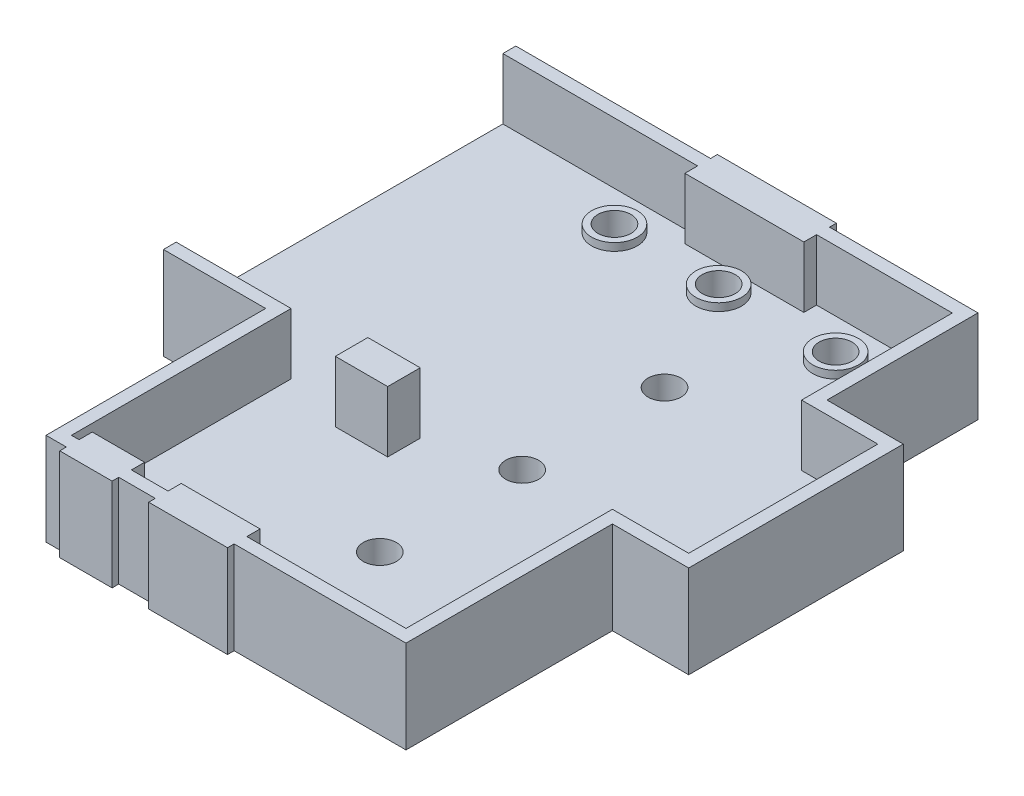
SolidWorks part; units mm, degrees
ref_plane "Спереди" through (0, 0, 0) normal (0, 0, 1) x (1, 0, 0)
ref_plane "Сверху" through (0, 0, 0) normal (0, 1, 0) x (1, 0, 0)
ref_plane "Справа" through (0, 0, 0) normal (1, 0, 0) x (0, 0, -1)
sketch "Эскиз2" plane through (0, 0, 0) normal (0, 1, 0) x (1, 0, 0)
  line L0 (0, 0) -> (-14310, 0) construction
  line L1 (0, 0) -> (0, -10805) construction
  line L2 (0, -3035) -> (-14310, -3035) construction
  line L3 (0, -6485) -> (-14310, -6485) construction
  line L4 (-1500, 0) -> (-1500, -10805) construction
  line L5 (-14310, 0) -> (-14310, -10805) construction
  line L6 (0, -10805) -> (-14310, -10805) construction
  dimension "D1" = 1500
  dimension "D2" = 12810
  dimension "D3" = 3035
  dimension "D4" = 3450
  dimension "D5" = 4320
sketch "Эскиз1" plane through (0, 0, 0) normal (0, 1, 0) x (1, 0, 0)
  line L0 (0, 0) -> (-14310, 0) construction
  line L1 (-1500, 0) -> (-1500, -10805) construction
  line L2 (0, -3035) -> (-14310, -3035) construction
  line L3 (0, 0) -> (0, -10805) construction
  line L4 (0, -6485) -> (-14310, -6485) construction
  line L5 (0, -10805) -> (-14310, -10805) construction
  line L6 (-8010, -6716.1927) -> (-8010, -6425)
  line L7 (-10270, 255) -> (-6440, 255)
  line L8 (-6440, 255) -> (-6440, 390)
  line L9 (-6440, 390) -> (-4100, 390)
  line L10 (-4100, 390) -> (-4100, 255)
  line L11 (-4100, 255) -> (-1180, 255)
  line L12 (-1180, 255) -> (-1180, -2715)
  line L13 (-1180, -2715) -> (320, -2715)
  line L14 (320, -2715) -> (320, -6935)
  line L15 (320, -6935) -> (-1180, -6935)
  line L16 (-1180, -6935) -> (-1180, -10995)
  line L17 (-10270, 255) -> (-10270, 0)
  line L18 (-10270, -6675) -> (-8260, -6675)
  line L19 (-8260, -6675) -> (-8260, -10995)
  line L20 (-1180, -10995) -> (-4560, -10995)
  line L21 (-4560, -10995) -> (-4560, -11125)
  line L22 (-4560, -11125) -> (-6110, -11125)
  line L23 (-6110, -11125) -> (-6110, -10995)
  line L24 (-6110, -10995) -> (-6830, -10995)
  line L25 (-6830, -10995) -> (-6830, -11125)
  line L26 (-6830, -11125) -> (-7860, -11125)
  line L27 (-7860, -11125) -> (-7860, -10995)
  line L28 (-7860, -10995) -> (-8260, -10995)
  line L29 (-10270, 0) -> (-6440, 0)
  line L30 (-1430, 0) -> (-1430, -2965)
  line L31 (-1430, -2965) -> (70, -2965)
  line L32 (70, -2965) -> (70, -6685)
  line L33 (70, -6685) -> (-1430, -6685)
  line L34 (-7860, -10745) -> (-8010, -10745)
  line L35 (-1430, -10745) -> (-4560, -10745)
  line L36 (-8010, -10745) -> (-8010, -6716.1927)
  line L37 (-10270, -6425) -> (-10270, -6675)
  line L38 (-6440, -250) -> (-6440, 0)
  line L39 (-8010, -6425) -> (-10270, -6425)
  line L40 (-6440, -250) -> (-4100, -250)
  line L41 (-7860, -10485) -> (-7860, -10745)
  line L42 (-6760, -6805) -> (-5730, -6805)
  line L43 (-6760, -6805) -> (-6760, -6165)
  line L44 (-6760, -6165) -> (-5730, -6165)
  line L45 (-5730, -6805) -> (-5730, -6165)
  line L46 (-1430, -6685) -> (-1430, -10745)
  line L47 (-4100, 0) -> (-4100, -250)
  line L48 (-4100, 0) -> (-1430, 0)
  line L49 (-6830, -10485) -> (-7860, -10485)
  line L50 (-6830, -10485) -> (-6830, -10745)
  line L51 (-6110, -10745) -> (-6830, -10745)
  line L52 (-6110, -10485) -> (-6110, -10745)
  line L53 (-4560, -10485) -> (-6110, -10485)
  line L54 (-4560, -10485) -> (-4560, -10745)
  dimension "D4" = 255
  dimension "D5" = 2600
  dimension "D6" = 320
  dimension "D7" = 135
  dimension "D8" = 135
  dimension "D9" = 250
  dimension "D10" = 320
  dimension "D11" = 250
  dimension "D12" = 320
  dimension "D13" = 250
  dimension "D14" = 450
  dimension "D15" = 2340
  dimension "D16" = 3830
  dimension "D17" = 250
  dimension "D18" = 250
  dimension "D19" = 130
  dimension "D20" = 130
  dimension "D21" = 1550
  dimension "D22" = 720
  dimension "D23" = 1030
  dimension "D24" = 400
  dimension "D25" = 320
  dimension "D26" = 190
  dimension "D27" = 640
  dimension "D28" = 250
  dimension "D29" = 250
  dimension "D30" = 1030
  dimension "D31" = 60
  dimension "D32" = 250
  dimension "D33" = 3380
  dimension "D34" = 320
  dimension "D35" = 320
  dimension "D36" = 1250
  dimension "D37" = 640
  dimension "D38" = 640
  dimension "D39" = 250
  dimension "D40" = 250
extrude "Бобышка-Вытянуть1" add sketch "Эскиз1" along normal blind 1820
sketch "Эскиз3" plane through (0, 0, 0) normal (0, 1, 0) x (1, 0, 0)
  line L0 (-10270, -6675) -> (-10270, 255)
  line L1 (-10270, 255) -> (-1180, 255)
  line L2 (-1180, 255) -> (-1180, -2715)
  line L3 (-1180, -2715) -> (320, -2715)
  line L4 (320, -2715) -> (320, -6935)
  line L5 (320, -6935) -> (-1180, -6935)
  line L6 (-1180, -6935) -> (-1180, -10995)
  line L7 (-1180, -10995) -> (-8260, -10995)
  line L8 (-8260, -10995) -> (-8260, -6675)
  line L9 (-8260, -6675) -> (-10270, -6675)
  line L10 (-10270, -6675) -> (-9970.5373, -6682.7722)
extrude "Бобышка-Вытянуть2" add sketch "Эскиз3" along normal blind 620 contours L9 L8 L7 L6 L5 L4 L3 L2 L1 L0
sketch "Эскиз5" plane through (0, 0, 0) normal (0, -1, 0) x (1, 0, 0)
  line L0 (-1500, 0) -> (-1500, 10805) construction
  line L1 (0, 0) -> (-14310, 0) construction
  circle A0 centre (-2970, 755) radius 450
  circle A1 centre (-5270, 755) radius 450
  circle A2 centre (-7320, 755) radius 450
  dimension "D3" = 900
  dimension "D4" = 900
  dimension "D5" = 900
  dimension "D6" = 1470
  dimension "D7" = 755
  dimension "D8" = 755
  dimension "D9" = 755
  dimension "D1" = 2300
  dimension "D2" = 2050
extrude "Бобышка-Вытянуть4" add sketch "Эскиз5" against normal blind 770
sketch "Эскиз6" plane through (0, 770, 0) normal (0, 1, 0) x (1, 0, 0)
  circle A0 centre (-7320, -755) radius 325
  circle A1 centre (-5270, -755) radius 325
  circle A2 centre (-2970, -755) radius 325
  dimension "D1" = 650
  dimension "D2" = 650
  dimension "D3" = 650
extrude "Вырез-Вытянуть1" cut sketch "Эскиз6" against normal through all
sketch "Эскиз7" plane through (0, 620, 0) normal (0, 1, 0) x (1, 0, 0)
  line L0 (-4190, -2900) -> (-4190, -8500) construction
  line L1 (0, 0) -> (-14310, 0) construction
  line L2 (-1500, 0) -> (-1500, -10805) construction
  circle A0 centre (-4190, -2900) radius 325
  circle A1 centre (-4190, -5700) radius 325
  circle A2 centre (-4190, -8500) radius 325
  dimension "D1" = 2900
  dimension "D2" = 2800
  dimension "D3" = 2800
  dimension "D4" = 650
  dimension "D5" = 650
  dimension "D6" = 650
  dimension "D7" = 2690
extrude "Вырез-Вытянуть2" cut sketch "Эскиз7" against normal through all
